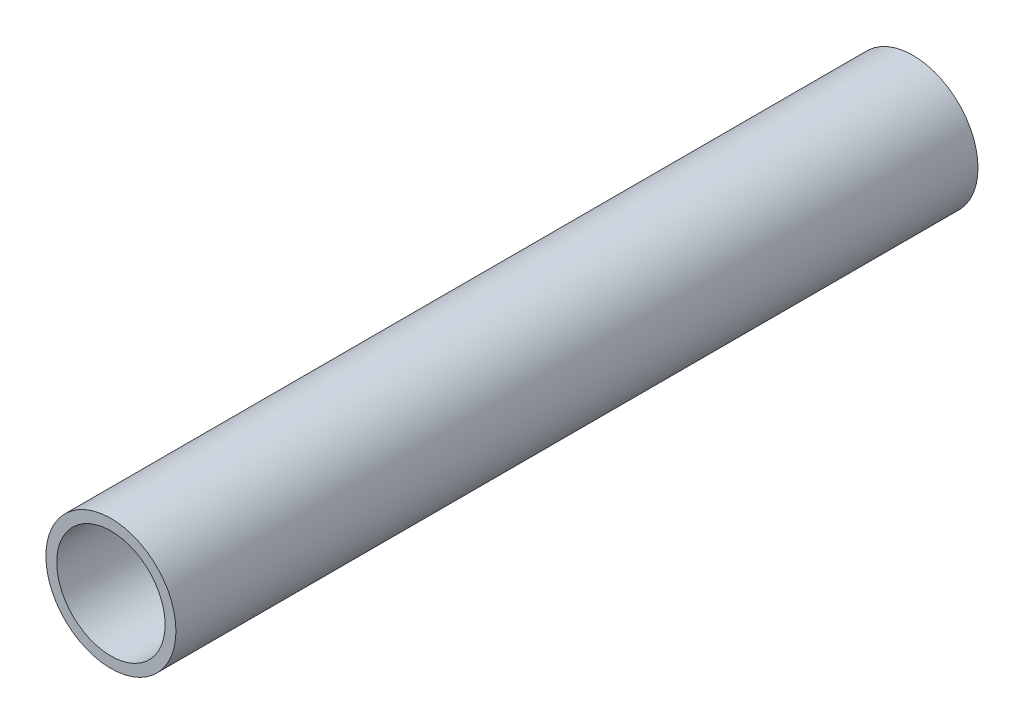
SolidWorks part; units mm, degrees
material "PVC Rigid"
ref_plane "Front Plane" through (0, 0, 0) normal (0, 0, 1) x (1, 0, 0)
ref_plane "Top Plane" through (0, 0, 0) normal (0, 1, 0) x (1, 0, 0)
ref_plane "Right Plane" through (0, 0, 0) normal (1, 0, 0) x (0, 0, -1)
sketch "Sketch2" plane through (0, 0, 0) normal (0, 0, 1) x (1, 0, 0)
  circle A0 centre (0, 0) radius 19.05
  circle A1 centre (0, 0) radius 15.875
  dimension "D1" = 38.1
  dimension "D2" = 31.75
extrude "Boss-Extrude1" add sketch "Sketch2" along normal blind 234.95
